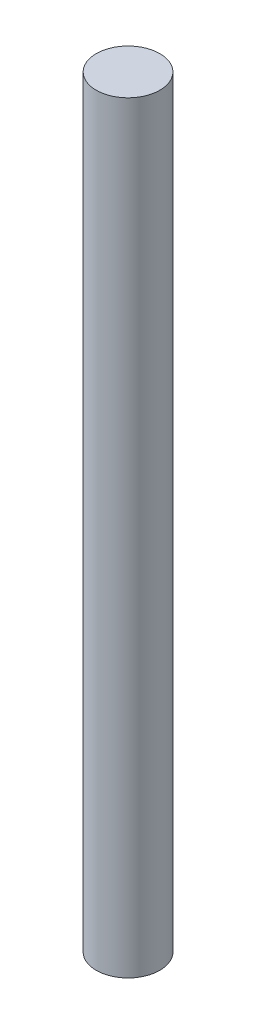
SolidWorks part; units mm, degrees
material "1060 Alloy"
ref_plane "Front Plane" through (0, 0, 0) normal (0, 0, 1) x (1, 0, 0)
ref_plane "Top Plane" through (0, 0, 0) normal (0, 1, 0) x (1, 0, 0)
ref_plane "Right Plane" through (0, 0, 0) normal (1, 0, 0) x (0, 0, -1)
sketch "Sketch1" plane through (0, 0, 0) normal (0, 0, 1) x (1, 0, 0)
  line L1 (0, 0) -> (6.35, 0)
  line L2 (0, 0) -> (0, 152.4)
  line L3 (0, 152.4) -> (6.35, 152.4)
  line L4 (6.35, 0) -> (6.35, 152.4)
  dimension "D1" = 152.4
  dimension "D2" = 6.35
revolve "Revolve1" add sketch "Sketch1" angle 360 about L2
